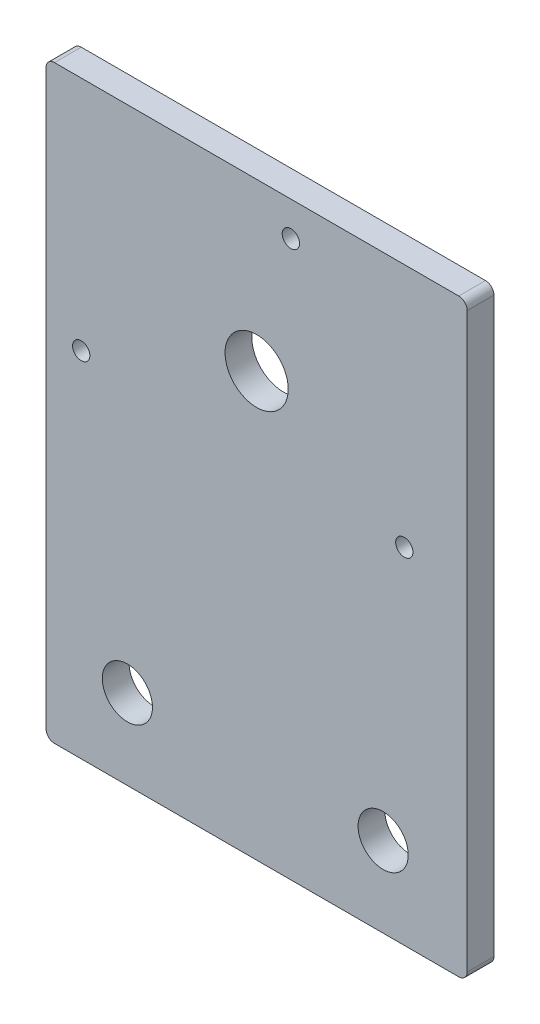
SolidWorks part; units mm, degrees
ref_plane "Front Plane" through (0, 0, 0) normal (0, 0, 1) x (1, 0, 0)
ref_plane "Top Plane" through (0, 0, 0) normal (0, 1, 0) x (1, 0, 0)
ref_plane "Right Plane" through (0, 0, 0) normal (1, 0, 0) x (0, 0, -1)
sketch "Sketch1" plane through (0, 0, 0) normal (0, 0, 1) x (1, 0, 0)
  line L0 (-30.6913, -50.95) -> (30.0409, -50.95) construction
  line L1 (-50, -70) -> (50, -70)
  line L2 (-50, -70) -> (-50, 70)
  line L3 (-50, 70) -> (50, 70)
  line L4 (50, -70) -> (50, 70)
  line L5 (-50, -70) -> (50, 70) construction
  line L6 (-50, 70) -> (50, -70) construction
  circle A0 centre (-30.6913, -50.95) radius 5.9538
  circle A1 centre (30.0409, -50.95) radius 5.9538
  circle A2 centre (-41.6505, 13.9227) radius 2.0548
  circle A3 centre (8.1225, 61.8691) radius 2.0548
  circle A4 centre (35.0638, 11.8678) radius 2.0548
  circle A5 centre (0, 30.582) radius 7.5
  point P0 (0, 0)
  point P6 (-30.6913, -50.95)
  point P7 (30.0409, -50.95)
  point P8 (8.1225, 61.8691)
  point P9 (-41.6505, 13.9227)
  point P10 (35.0638, 11.8678)
  point P21 (0, 30.582)
  dimension "D4" = 15
  dimension "D1" = 100
  dimension "D2" = 140
  dimension "D3" = 19.05
extrude "Boss-Extrude1" add sketch "Sketch1" along normal blind 6.35
fillet "Fillet1" radius 2 4 edges at (-50, -70, 3.175) (50, -70, 3.175) (50, 70, 3.175) (-50, 70, 3.175)
equation "\"tubeStockHeight\"= 1.5 * 25.4mm"
equation "\"D3@Sketch1\"=\"tubeStockHeight\"/2"
equation "\"motorShaftDiameter\"= 10mm"
equation "\"D4@Sketch1\"=\"motorShaftDiameter\"+5"
